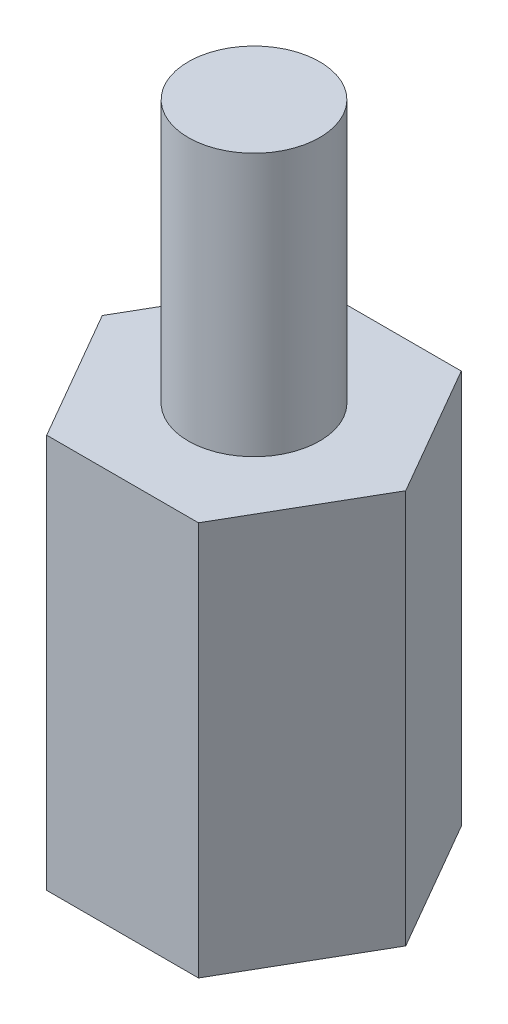
SolidWorks part; units mm, degrees
ref_plane "前视基准面" through (0, 0, 0) normal (0, 0, 1) x (1, 0, 0)
ref_plane "上视基准面" through (0, 0, 0) normal (0, 1, 0) x (1, 0, 0)
ref_plane "右视基准面" through (0, 0, 0) normal (1, 0, 0) x (0, 0, -1)
sketch "草图1" plane through (0, 0, 0) normal (0, 1, 0) x (1, 0, 0)
  line L1 (2.3094, 0) -> (1.1547, 2)
  line L2 (1.1547, 2) -> (-1.1547, 2)
  line L3 (-1.1547, 2) -> (-2.3094, 0)
  line L4 (-2.3094, 0) -> (-1.1547, -2)
  line L5 (-1.1547, -2) -> (1.1547, -2)
  line L6 (1.1547, -2) -> (2.3094, 0)
  circle A0 centre (0, 0) radius 2 construction
  dimension "D1" = 4
extrude "凸台-拉伸1" add sketch "草图1" along normal blind 6
sketch "草图2" plane through (0, 6, 0) normal (0, 1, 0) x (1, 0, 0)
  circle A0 centre (0, 0) radius 1
  dimension "D1" = 2
extrude "凸台-拉伸2" add sketch "草图2" along normal blind 4
sketch "草图3" plane through (0, 0, 0) normal (0, -1, 0) x (1, 0, 0)
  circle A0 centre (0, 0) radius 1
  dimension "D1" = 2
extrude "切除-拉伸1" cut sketch "草图3" against normal blind 4
